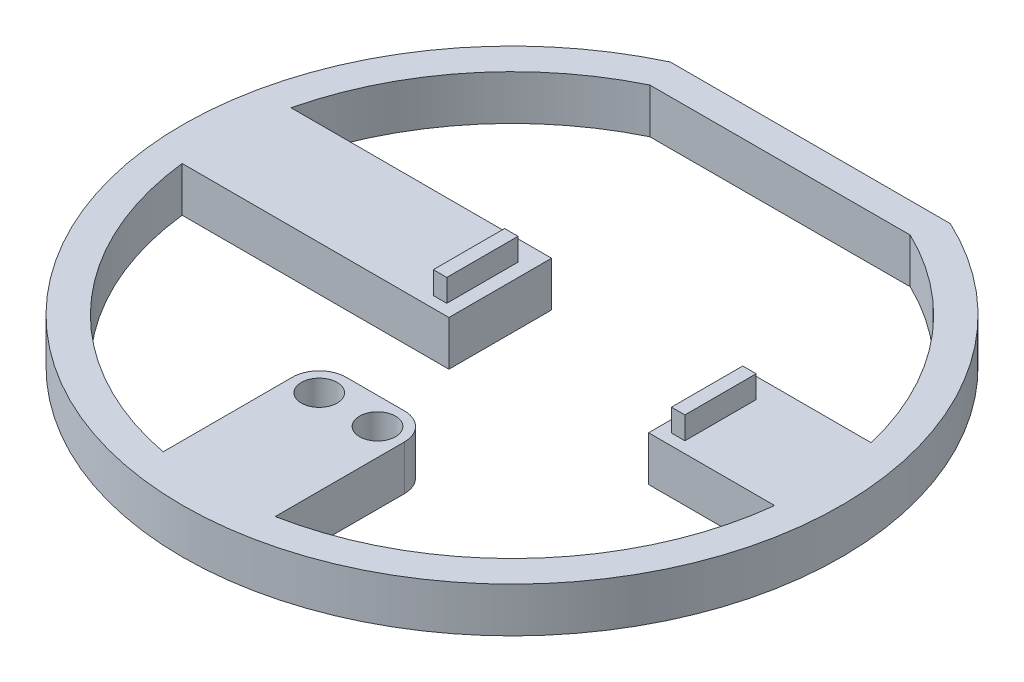
SolidWorks part; units mm, degrees
ref_plane "Front Plane" through (0, 0, 0) normal (0, 0, 1) x (1, 0, 0)
ref_plane "Top Plane" through (0, 0, 0) normal (0, 1, 0) x (1, 0, 0)
ref_plane "Right Plane" through (0, 0, 0) normal (1, 0, 0) x (0, 0, -1)
sketch "Sketch1" plane through (0, 0, 0) normal (0, 1, 0) x (1, 0, 0)
  line L0 (-15.5673, 33.7491) -> (15.645, 33.7491)
  line L1 (-14.4939, 30.3832) -> (14.511, 30.4126)
  line L2 (38.2153, -17.7727) -> (-40.1019, -17.7727) construction
  line L5 (23.0658, 8.1773) -> (-7.4881, 8.1773) construction
  line L6 (-7.4881, -3.2727) -> (23.0658, -3.2727) construction
  line L9 (-3.25, -3.2727) -> (-3.25, 8.1773)
  line L10 (19.0142, -3.2727) -> (19.0142, 8.1773)
  line L13 (6.2888, -32.18) -> (6.2888, -17.7727)
  line L14 (-6.2112, -17.7727) -> (-6.2112, -32.18)
  line L15 (-3.2112, -14.7727) -> (3.2888, -14.7727)
  line L18 (-3.25, -3.2727) -> (-32.999, -3.2727)
  line L19 (-32.3073, 8.1773) -> (-3.25, 8.1773)
  line L20 (19.0142, 8.1773) -> (32.385, 8.1773)
  line L21 (19.0142, -3.2727) -> (33.0767, -3.2727)
  arc A0 (15.645, 33.7491) -> (-15.5673, 33.7491) centre (0.0388, 0.4773) cw
  circle A2 centre (-3.2112, -17.7727) radius 2
  circle A3 centre (3.2888, -17.7727) radius 2
  arc A7 (-6.2112, -17.7727) -> (-3.2112, -14.7727) centre (-3.2112, -17.7727) cw
  arc A8 (6.2888, -17.7727) -> (3.2888, -14.7727) centre (3.2888, -17.7727) ccw
  arc A9 (-14.4939, 30.3832) -> (-32.3073, 8.1773) centre (0.0388, 0.4773) ccw
  arc A11 (14.511, 30.4126) -> (32.385, 8.1773) centre (0.0388, 0.4773) cw
  arc A12 (-32.999, -3.2727) -> (-6.2112, -32.18) centre (0.0388, 0.4773) ccw
  arc A13 (33.0767, -3.2727) -> (6.2888, -32.18) centre (0.0388, 0.4773) cw
  point P9 (0.0388, -36.2727)
  dimension "D1" = 36.75
  dimension "D2" = 6.5
  dimension "D7" = 4
  dimension "D9" = 33.25
  dimension "D3" = 18.5
  dimension "D4" = 14.5
  dimension "D5" = 3
  dimension "D6" = 3
extrude "Boss-Extrude1" add sketch "Sketch1" along normal blind 5
sketch "Sketch4" plane through (0, 5, 0) normal (0, 1, 0) x (1, 0, 0)
  line L1 (21.8158, -2.0227) -> (20.3158, -2.0227)
  line L2 (21.8158, -2.0227) -> (21.8158, 5.9273)
  line L3 (21.8158, 5.9273) -> (20.3158, 5.9273)
  line L4 (20.3158, -2.0227) -> (20.3158, 5.9273)
  line L5 (-6.2381, -2.0227) -> (-4.7381, -2.0227)
  line L6 (-6.2381, -2.0227) -> (-6.2381, 5.9273)
  line L7 (-6.2381, 5.9273) -> (-4.7381, 5.9273)
  line L8 (-4.7381, -2.0227) -> (-4.7381, 5.9273)
  line L14 (20.0658, 6.1773) -> (22.0658, 6.1773) construction
  line L15 (22.0658, 6.1773) -> (22.0658, -2.2727) construction
  line L16 (20.0658, -2.2727) -> (20.0658, 6.1773) construction
  line L17 (22.0658, -2.2727) -> (20.0658, -2.2727) construction
  line L18 (-6.4881, -2.2727) -> (-6.4881, 6.1773) construction
  line L19 (-6.4881, 6.1773) -> (-4.4881, 6.1773) construction
  line L20 (-4.4881, 6.1773) -> (-4.4881, 2.7585) construction
  line L21 (-4.4881, -2.2727) -> (-6.4881, -2.2727) construction
  dimension "D1" = 0.25
  dimension "D2" = 0.25
  dimension "D3" = 0.25
  dimension "D4" = 0.25
  dimension "D5" = 0.25
  dimension "D6" = 0.25
  dimension "D7" = 0.25
  dimension "D8" = 0.25
extrude "Boss-Extrude2" add sketch "Sketch4" along normal blind 2.5
